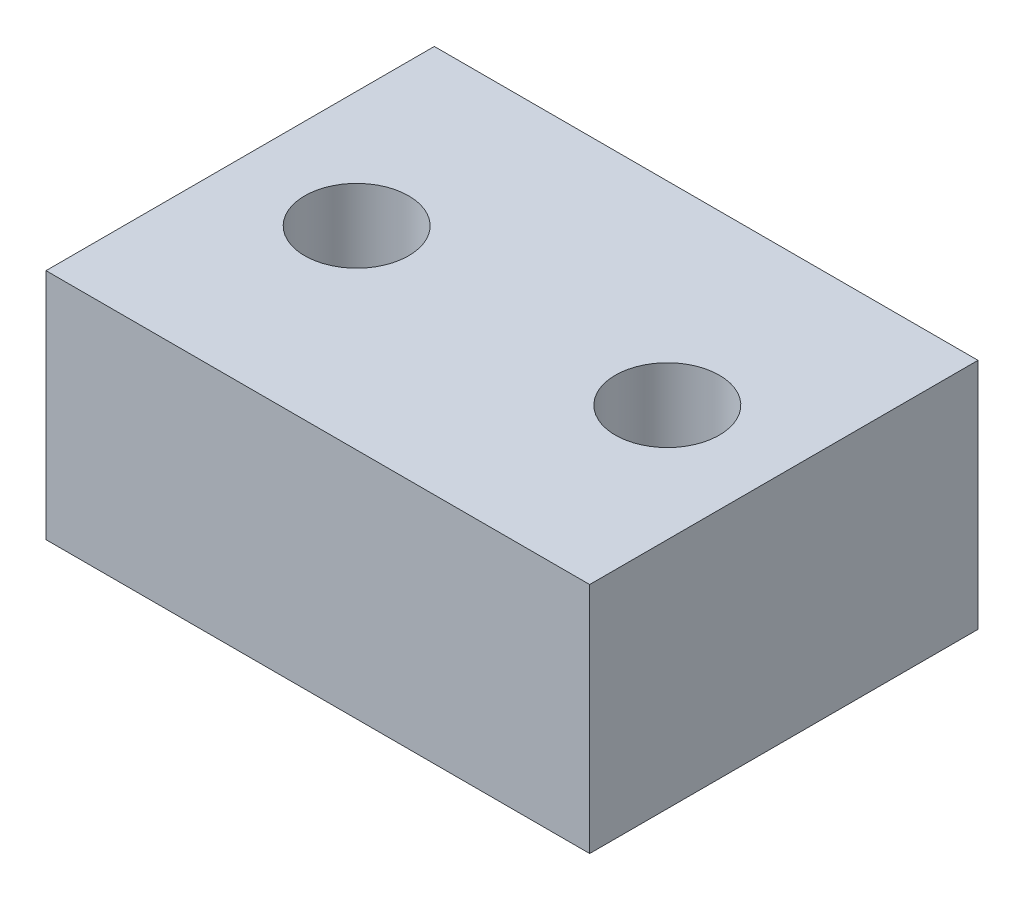
SolidWorks part; units mm, degrees
ref_plane "Front Plane" through (0, 0, 0) normal (0, 0, 1) x (1, 0, 0)
ref_plane "Top Plane" through (0, 0, 0) normal (0, 1, 0) x (1, 0, 0)
ref_plane "Right Plane" through (0, 0, 0) normal (1, 0, 0) x (0, 0, -1)
sketch "Sketch1" plane through (0, 0, 0) normal (0, 1, 0) x (1, 0, 0)
  line L0 (3.81, 6.35) -> (13.97, 6.35) construction
  line L1 (0, 0) -> (17.78, 0)
  line L2 (0, 0) -> (0, 12.7)
  line L3 (0, 12.7) -> (17.78, 12.7)
  line L4 (17.78, 0) -> (17.78, 12.7)
  line L5 (8.89, 12.7) -> (8.89, 0) construction
  circle A0 centre (3.81, 6.35) radius 1.7
  circle A1 centre (13.97, 6.35) radius 1.7
  point P11 (8.89, 6.35)
  point P12 (8.89, 6.35)
  point P13 (14.1627, 6.35)
  dimension "D2" = 3.4
  dimension "D1" = 12.7
  dimension "D3" = 17.78
  dimension "D4" = 10.16
extrude "Boss-Extrude1" add sketch "Sketch1" along normal blind 7.62
